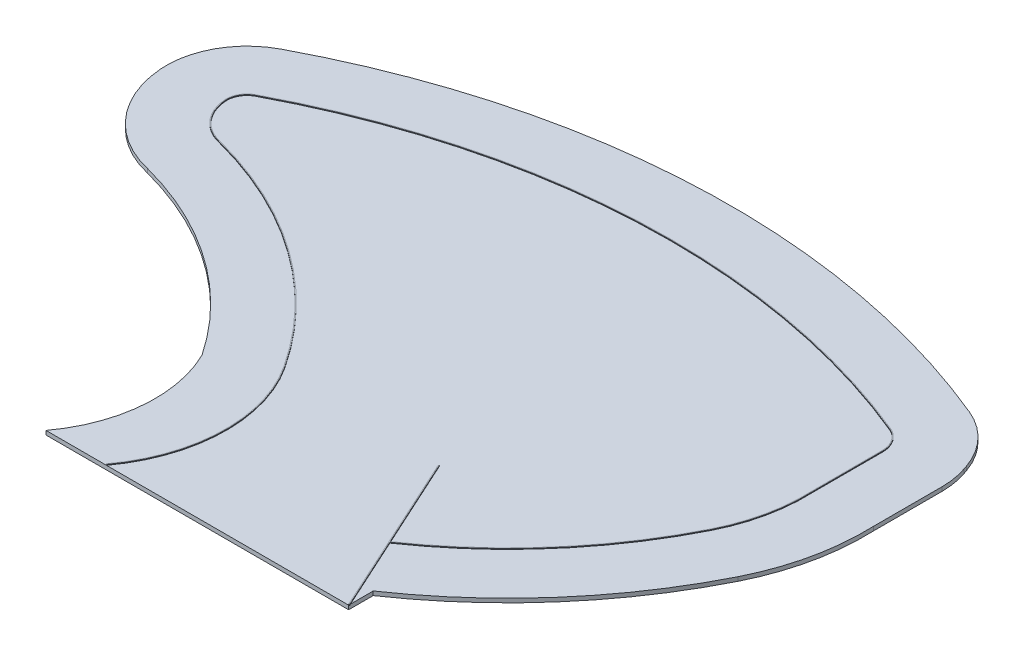
SolidWorks part; units mm, degrees
ref_plane "Front Plane" through (0, 0, 0) normal (0, 0, 1) x (1, 0, 0)
ref_plane "Top Plane" through (0, 0, 0) normal (0, 1, 0) x (1, 0, 0)
ref_plane "Right Plane" through (0, 0, 0) normal (1, 0, 0) x (0, 0, -1)
sketch "Sketch2" plane through (0, 0, 0) normal (0, 1, 0) x (1, 0, 0)
  line L0 (55.428, -792.898) -> (95.428, -792.898) construction
  line L1 (83.6142, 6.6908) -> (143.6142, 6.6908)
  dimension "D1" = 60
sketch "Sketch3" plane through (0, 0, 0) normal (0, 1, 0) x (1, 0, 0)
  line L0 (143.6142, 12.7786) -> (143.6142, 6.6908)
  line L2 (83.6142, 6.6908) -> (143.6142, 6.6908) construction
  line L3 (83.6142, 6.6908) -> (143.6142, 6.6908)
  line L4 (83.6142, 6.6908) -> (68.6142, 6.6908)
  line L5 (191.7256, 88.676) -> (191.7256, 105.6462)
  line L7 (190.2906, 113.1536) -> (190.6216, 112.1991)
  arc A3 (15.8669, 117.6272) -> (179.0708, 125.0688) centre (105.3829, -52.2171) cw
  arc A4 (191.7256, 88.676) -> (185.7403, 61.0245) centre (134.7126, 86.5432) cw
  arc A5 (143.6142, 12.7786) -> (185.7403, 61.0245) centre (71.7792, 118.0158) ccw
  arc A8 (68.6142, 6.6908) -> (71.7792, 42.1924) centre (41.0768, 27.0377) ccw
  arc A9 (71.7792, 42.1924) -> (24.9056, 75.5028) centre (4.1864, -3.2878) ccw
  arc A10 (24.9056, 75.5028) -> (5.2478, 98.44) centre (30.682, 100.3455) cw
  arc A11 (179.0708, 125.0688) -> (190.2906, 113.1536) centre (171.3946, 106.6006) cw
  arc A12 (191.7256, 105.6462) -> (190.6216, 112.1991) centre (171.7256, 105.6462) ccw
  arc A13 (15.8669, 117.6272) -> (5.2478, 98.44) centre (25.192, 99.9342) ccw
  dimension "D1" = 20
  dimension "D2" = 20
  dimension "D3" = 20
sketch "Sketch6" plane through (0, 0, 0) normal (0, 1, 0) x (1, 0, 0)
  line L0 (176.7256, 82.7901) -> (134.2503, 27.1497) construction
  line L1 (83.6142, 6.6908) -> (143.6142, 6.6908) construction
  line L3 (83.6142, 6.6908) -> (83.6142, 46.6908) construction
  line L4 (176.7256, 88.3742) -> (176.7256, 105.6462)
  line L5 (176.7256, 88.3742) -> (176.7256, 105.6462)
  line L6 (83.6142, 6.6908) -> (143.6142, 6.6908) construction
  line L7 (32.0075, 143.7674) -> (32.0075, 97.0828) construction
  line L8 (32.0075, 120.4251) -> (83.6142, 46.6908) construction
  line L9 (176.7256, 82.7901) -> (131.9801, 122.7632) construction
  line L10 (131.9801, 122.7632) -> (32.0075, 120.4251) construction
  line L11 (143.6142, 6.6908) -> (124.8864, 47.6087)
  arc A0 (84.7538, 49.7708) -> (83.6142, 6.6908) centre (53.2872, 29.0481) cw
  arc A1 (173.3136, 111.2177) -> (176.7256, 105.6462) centre (170.5894, 105.7189) cw
  arc A77 (176.1186, 108.2388) -> (173.3136, 111.2177) centre (171.3946, 106.6006) ccw
  arc A78 (173.3136, 111.2177) -> (22.8607, 104.3575) centre (105.3829, -52.2171) ccw
  arc A79 (22.8607, 104.3575) -> (20.2059, 99.5607) centre (25.192, 99.9342) ccw
  arc A80 (20.2059, 99.5607) -> (28.4585, 90.0781) centre (30.682, 100.3455) ccw
  arc A81 (84.7538, 49.7708) -> (28.4585, 90.0781) centre (4.1864, -3.2878) ccw
  arc A82 (80.6783, -2.2231) -> (84.7538, 49.7708) centre (41.0768, 27.0377) ccw
  arc A84 (173.3136, 111.2177) -> (22.8607, 104.3575) centre (105.3829, -52.2171) ccw
  arc A85 (22.8607, 104.3575) -> (20.2059, 99.5607) centre (25.192, 99.9342) ccw
  arc A86 (20.2059, 99.5607) -> (28.4585, 90.0781) centre (30.682, 100.3455) ccw
  arc A87 (84.7538, 49.7708) -> (28.4585, 90.0781) centre (4.1864, -3.2878) ccw
  arc A93 (176.7256, 105.6462) -> (176.4496, 107.2844) centre (171.7256, 105.6462) ccw
  arc A94 (172.3244, 67.7337) -> (176.7256, 88.3742) centre (134.7126, 86.5432) ccw
  arc A95 (135.1576, 25.1675) -> (172.3244, 67.7337) centre (71.7792, 118.0158) ccw
  arc A97 (172.3244, 67.7337) -> (176.7256, 88.3742) centre (134.7126, 86.5432) ccw
  arc A98 (135.1576, 25.1675) -> (172.3244, 67.7337) centre (71.7792, 118.0158) ccw
  dimension "D3" = 40
  dimension "D4" = 60
  dimension "D5" = 100
  dimension "D6" = 90
  dimension "D7" = 45
  dimension "D8" = 70
  dimension "D9" = 60
  dimension "D1" = 15
  dimension "D2" = 15
extrude "Boss-Extrude1" add sketch "Sketch3" along normal blind 1
extrude "Extrude-Thin1" add sketch "Sketch6" along normal blind 0.2 from surface at 1 thin
